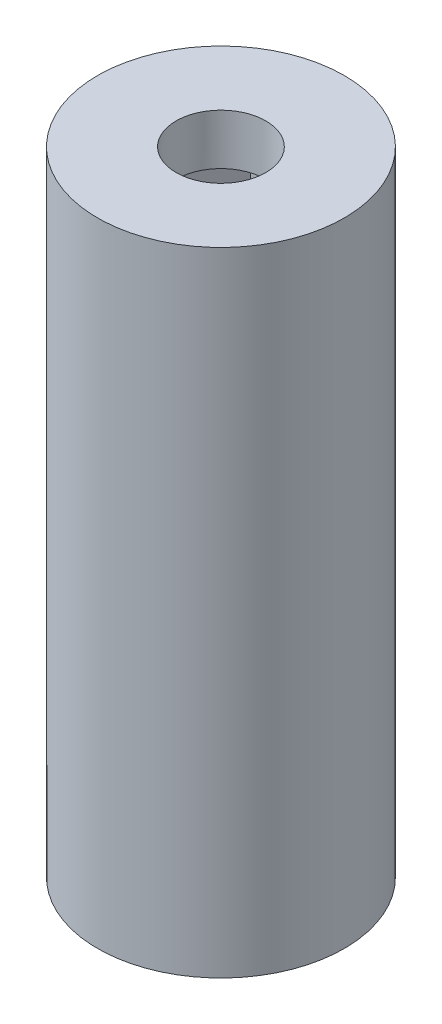
SolidWorks part; units mm, degrees
ref_plane "Front Plane" through (0, 0, 0) normal (0, 0, 1) x (1, 0, 0)
ref_plane "Top Plane" through (0, 0, 0) normal (0, 1, 0) x (1, 0, 0)
ref_plane "Right Plane" through (0, 0, 0) normal (1, 0, 0) x (0, 0, -1)
sketch "Sketch1" plane through (0, 0, 0) normal (1, 0, 0) x (0, 0, -1)
  line L0 (0, 0) -> (0, 25.4) construction
  line L1 (0, 25.4) -> (9.9441, 25.4)
  line L2 (9.9441, 25.4) -> (9.9441, 23.368)
  line L3 (9.9441, 23.368) -> (4.953, 23.368)
  line L4 (4.953, 23.368) -> (4.953, 0)
  line L5 (4.953, 0) -> (0, 0)
  line L6 (0, 0) -> (0, 25.4)
  dimension "D1" = 2.032
  dimension "D2" = 25.4
  dimension "D3" = 19.8882
  dimension "D4" = 9.906
revolve "Revolve1" add sketch "Sketch1" angle 360 about L0
sketch "Sketch2" plane through (0, 25.4, 0) normal (0, 1, 0) x (1, 0, 0)
  circle A0 centre (0, 0) radius 1.397
  dimension "D1" = 2.794
sketch "Sketch4" plane through (0, 0, 0) normal (0, -1, 0) x (1, 0, 0)
  line L0 (0, 0) -> (3.2262, 0) construction
  line L1 (1.6131, -2.794) -> (3.2262, 0)
  line L2 (3.2262, 0) -> (1.6131, 2.794)
  line L3 (1.6131, 2.794) -> (-1.6131, 2.794)
  line L4 (-1.6131, 2.794) -> (-3.2262, 0)
  line L5 (-3.2262, 0) -> (-1.6131, -2.794)
  line L6 (-1.6131, -2.794) -> (1.6131, -2.794)
  circle A0 centre (0, 0) radius 4.1275 construction
  circle A1 centre (0, 0) radius 2.794 construction
  dimension "D1" = 8.255
  dimension "D2" = 5.588
extrude "Cut-Extrude2" cut sketch "Sketch4" against normal up to surface (23.368 mm away) up to face at (0, 23.368, -9.9441)
sketch "Sketch5" plane through (0, 25.4, 0) normal (0, 1, 0) x (1, 0, 0)
  circle A0 centre (0, 0) radius 6.985 construction
  circle A1 centre (0, 6.985) radius 1.27
  circle A2 centre (6.985, 0) radius 1.27
  circle A3 centre (0, -6.985) radius 1.27
  circle A4 centre (-6.985, 0) radius 1.27
  dimension "D1" = 13.97
  dimension "D2" = 2.54
  dimension "D3" = 4
hole_wizard "M3 Clearance Hole1" positions "Sketch8" profile "Sketch9" hole size "M3" standard "ANSI Metric" end condition through all
sketch "Sketch8" plane through (0, 25.4, 0) normal (0, 1, 0) x (1, 0, 0)
  point P0 (-6.985, 0)
  point P3 (0, 0)
  point P6 (6.985, 0)
  point P9 (0, 6.985)
  point P12 (0, -6.985)
sketch "Sketch9" plane through (-6.985, 25.4, 0) normal (1, 0, 0) x (0, 0, 1)
  line L0 (0, 0) -> (0, 25.4)
  line L1 (0, 25.4) -> (1.8, 25.4)
  line L2 (1.8, 25.4) -> (1.8, 0)
  line L5 (1.8, 0) -> (0, 0)
  line L11 (0, -6.35) -> (0, 107.95) construction
  dimension "Thru Hole Dia." = 3.6
  dimension "Thru Hole Depth" = 25.4
sketch "Sketch10" plane through (0, 0, 0) normal (0, -1, 0) x (1, 0, 0)
  circle A0 centre (0, 0) radius 4.953 construction
  circle A1 centre (0, 0) radius 4.953
extrude "Cut-Extrude3" cut sketch "Sketch10" against normal through all flip side to cut
